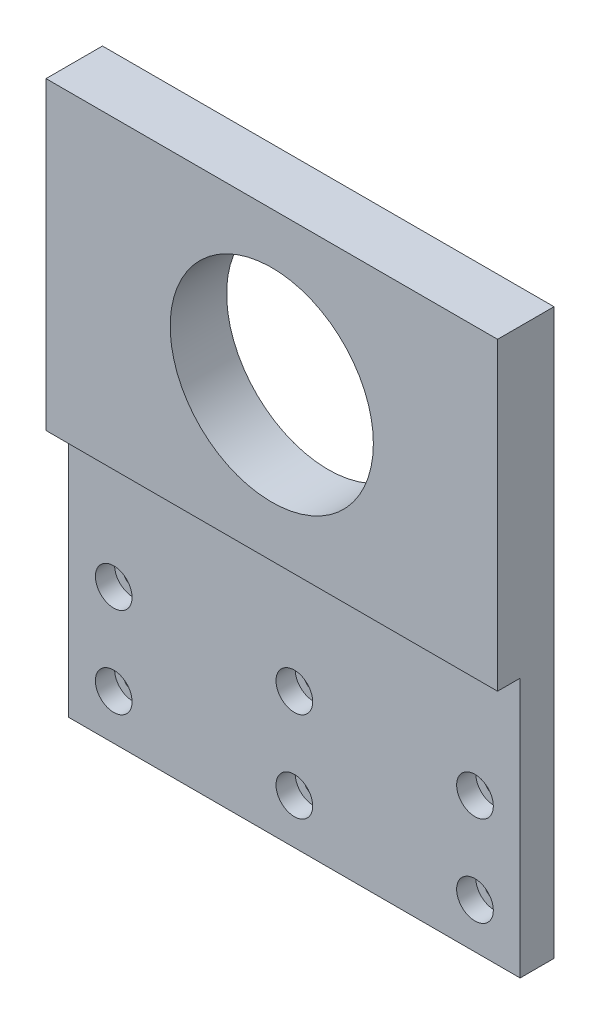
SolidWorks part; units mm, degrees
ref_plane "Front Plane" through (0, 0, 0) normal (0, 0, 1) x (1, 0, 0)
ref_plane "Top Plane" through (0, 0, 0) normal (0, 1, 0) x (1, 0, 0)
ref_plane "Right Plane" through (0, 0, 0) normal (1, 0, 0) x (0, 0, -1)
sketch "Sketch1" plane through (0, 0, 0) normal (0, 0, 1) x (1, 0, 0)
  line L1 (0, 0) -> (80, 0)
  line L2 (0, 0) -> (0, 100)
  line L3 (0, 100) -> (80, 100)
  line L4 (80, 0) -> (80, 100)
  dimension "D1" = 80
  dimension "D2" = 100
extrude "Boss-Extrude1" add sketch "Sketch1" along normal blind 10
sketch "Sketch2" plane through (0, 0, 10) normal (0, 0, 1) x (1, 0, 0)
  line L0 (40, 100) -> (40, -6.8876) construction
  line L1 (80, 100) -> (0, 100) construction
  line L2 (0, 0) -> (80, 0) construction
  circle A0 centre (40, 73) radius 18
  dimension "D1" = 36
  dimension "D2" = 73
extrude "Cut-Extrude1" cut sketch "Sketch2" against normal through all
sketch "Sketch3" plane through (0, 0, 10) normal (0, 0, 1) x (1, 0, 0)
  line L0 (80, 0) -> (80, 100) construction
  line L1 (0, 0) -> (80, 0)
  line L2 (0, 0) -> (0, 46)
  line L3 (0, 46) -> (80, 46)
  line L4 (80, 0) -> (80, 46)
  line L5 (40, 46) -> (40, 100) construction
  line L6 (80, 100) -> (0, 100) construction
  circle A0 centre (40, 73) radius 18 construction
  point P7 (0, 0)
  point P13 (40, 73)
extrude "Cut-Extrude2" cut sketch "Sketch3" against normal blind 4
sketch "Sketch4" plane through (0, 0, 6) normal (0, 0, 1) x (1, 0, 0)
  line L0 (0, 0) -> (80, 0) construction
  line L1 (0, 46) -> (0, 0) construction
  line L2 (80, 0) -> (80, 46) construction
  point P0 (8, 8)
  point P11 (40, 8)
  point P12 (72, 8)
  point P13 (40, 24)
  point P14 (72, 24)
  point P15 (8, 24)
  dimension "D1" = 8
  dimension "D2" = 8
  dimension "D5" = 8
  dimension "D6" = 16
  dimension "D4" = 3
  dimension "D3" = 2
hole_wizard "CBORE for M3 Hex Socket Head Cap Screw1" positions "Sketch4" profile "Sketch5" counterbore size "M3" standard "DIN" end condition through all
sketch "Sketch5" plane through (8, 8, 6) normal (1, 0, 0) x (0, -1, 0)
  line L0 (0, 0) -> (0, 6)
  line L1 (0, 6) -> (1.7, 6)
  line L3 (1.7, 6) -> (1.7, 3.4)
  line L4 (1.7, 3.4) -> (3.25, 3.4)
  line L5 (3.25, 3.4) -> (3.25, 0)
  line L7 (3.25, 0) -> (0, 0)
  line L11 (0, -6.35) -> (0, 107.95) construction
  dimension "Thru Hole Dia." = 3.4
  dimension "Thru Hole Depth" = 6
  dimension "C'Bore Dia." = 6.5
  dimension "C'Bore Depth" = 3.4
